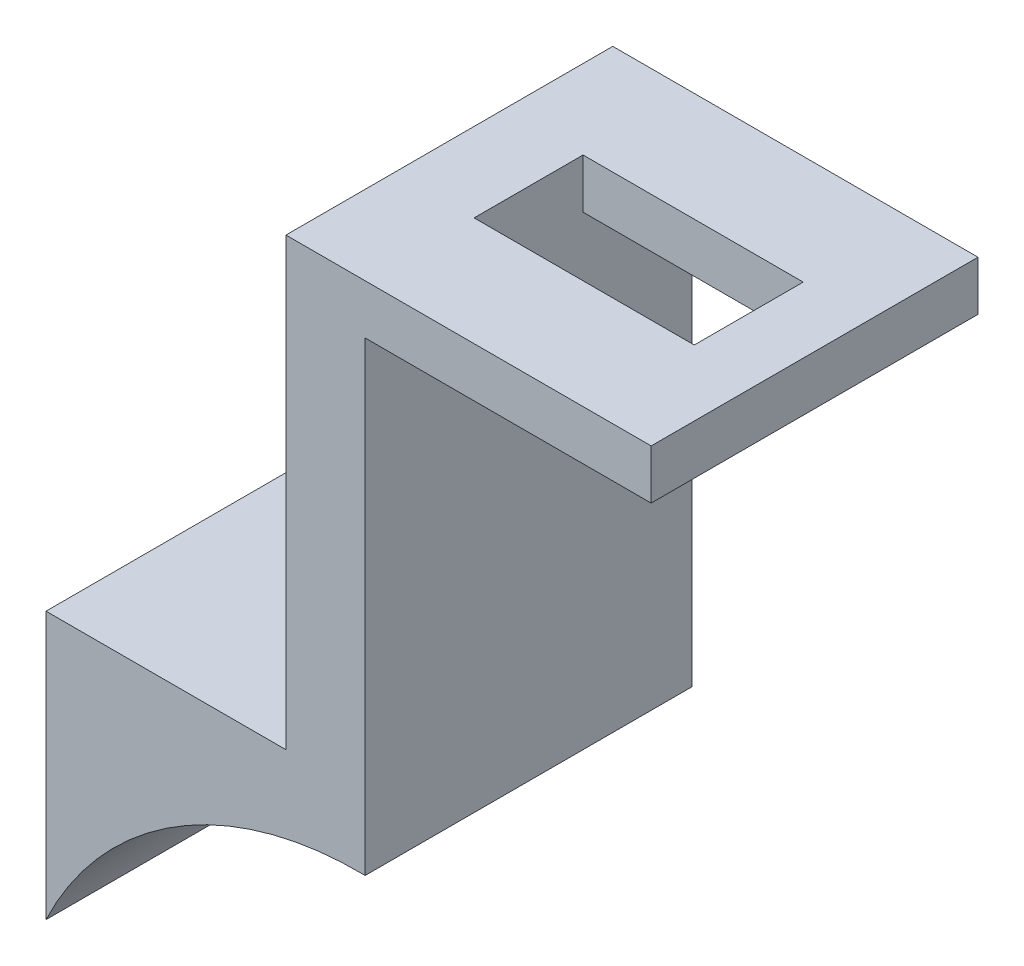
SolidWorks part; units mm, degrees
ref_plane "Front Plane" through (0, 0, 0) normal (0, 0, 1) x (1, 0, 0)
ref_plane "Top Plane" through (0, 0, 0) normal (0, 1, 0) x (1, 0, 0)
ref_plane "Right Plane" through (0, 0, 0) normal (1, 0, 0) x (0, 0, -1)
sketch "Sketch1" plane through (0, 0, 0) normal (0, 0, 1) x (1, 0, 0)
  line L0 (-20.327, 19.1977) -> (16.548, 19.1977)
  line L1 (16.548, 19.1977) -> (16.548, 14.1977)
  line L2 (16.548, 14.1977) -> (-12.327, 14.1977)
  line L6 (-12.327, -32.8023) -> (-12.327, 14.1977)
  line L7 (-20.327, 19.1977) -> (-20.327, 14.1977)
  line L9 (-20.327, 14.1977) -> (-20.327, -25.8023)
  line L10 (-20.327, -25.8023) -> (-44.552, -25.8023)
  line L11 (-44.552, -25.8023) -> (-44.552, -52.7773)
  arc A0 (-44.552, -52.7773) -> (-12.327, -32.8023) centre (-12.9385, -67.797) cw
  dimension "D7" = 35
  dimension "D1" = 40
  dimension "D2" = 36.875
  dimension "D3" = 5
  dimension "D4" = 47
  dimension "D5" = 24.225
  dimension "D6" = 26.975
extrude "Boss-Extrude1" add sketch "Sketch1" along normal blind 33
sketch "Sketch2" plane through (0, 19.1977, 0) normal (0, 1, 0) x (1, 0, 0)
  line L0 (16.548, -33) -> (-20.327, -33) construction
  line L1 (-12.327, -33) -> (-12.327, 0) construction
  line L2 (16.548, 0) -> (-20.327, 0) construction
  line L3 (9.9005, -33) -> (9.9005, 0) construction
  line L4 (-12.327, -11) -> (9.9005, -11)
  line L5 (9.9005, -11) -> (9.9005, -22)
  line L6 (9.9005, -22) -> (-12.327, -22)
  line L7 (-12.327, -22) -> (-12.327, -11)
  point P0 (-12.327, -33)
  point P1 (9.9005, -33)
  dimension "D1" = 11
  dimension "D2" = 6.6475
  dimension "D3" = 11
extrude "Cut-Extrude1" cut sketch "Sketch2" against normal blind 10 and the other way through all
sketch "Sketch3" plane through (-44.552, 0, 0) normal (-1, 0, 0) x (0, 0, 1)
  line L0 (33, -52.7773) -> (0, -52.7773) construction
  circle A0 centre (16.5, -40.7773) radius 1.5
  circle A1 centre (16.5, -30.7773) radius 1.5
  dimension "D1" = 3
  dimension "D2" = 3
  dimension "D3" = 12
  dimension "D4" = 22
extrude "Cut-Extrude2" cut sketch "Sketch3" against normal blind 8
